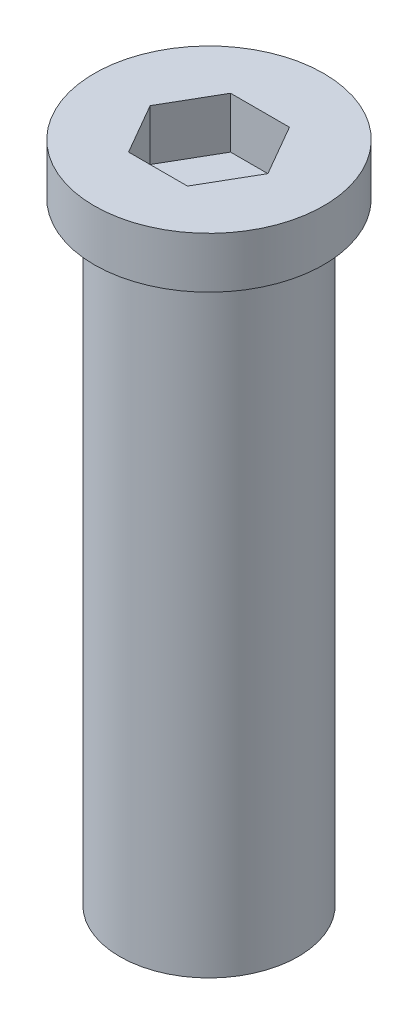
SolidWorks part; units mm, degrees
material "AISI 304"
ref_plane "Front Plane" through (0, 0, 0) normal (0, 0, 1) x (1, 0, 0)
ref_plane "Top Plane" through (0, 0, 0) normal (0, 1, 0) x (1, 0, 0)
ref_plane "Right Plane" through (0, 0, 0) normal (1, 0, 0) x (0, 0, -1)
sketch "Sketch1" plane through (0, 0, 0) normal (0, 1, 0) x (1, 0, 0)
  circle A0 centre (0, 0) radius 1.75
  dimension "D1" = 3.5
extrude "Boss-Extrude1" add sketch "Sketch1" along normal mid plane 12
sketch "Sketch2" plane through (0, 6, 0) normal (0, 1, 0) x (1, 0, 0)
  circle A0 centre (0, 0) radius 2.25
  dimension "D1" = 4.5
extrude "Boss-Extrude2" add sketch "Sketch2" along normal blind 1
sketch "Sketch3" plane through (0, 7, 0) normal (0, 1, 0) x (1, 0, 0)
  line L0 (0.5774, 1) -> (1.1547, 0)
  line L1 (0.5774, 1) -> (-0.5774, 1)
  line L2 (-0.5774, 1) -> (-1.1547, 0)
  line L3 (-1.1547, 0) -> (1.1547, 0) construction
  line L4 (0.5774, -1) -> (1.1547, 0)
  line L5 (0.5774, -1) -> (-0.5774, -1)
  line L6 (-0.5774, -1) -> (-1.1547, 0)
  circle A0 centre (0, 0) radius 1 construction
  point P4 (0, 0)
  dimension "D1" = 2
  dimension "D2" = 1.1547
  dimension "D4" = 1.1547
extrude "Cut-Extrude1" cut sketch "Sketch3" against normal blind 1 contours L4 L0 L1 L2 L6 L5
